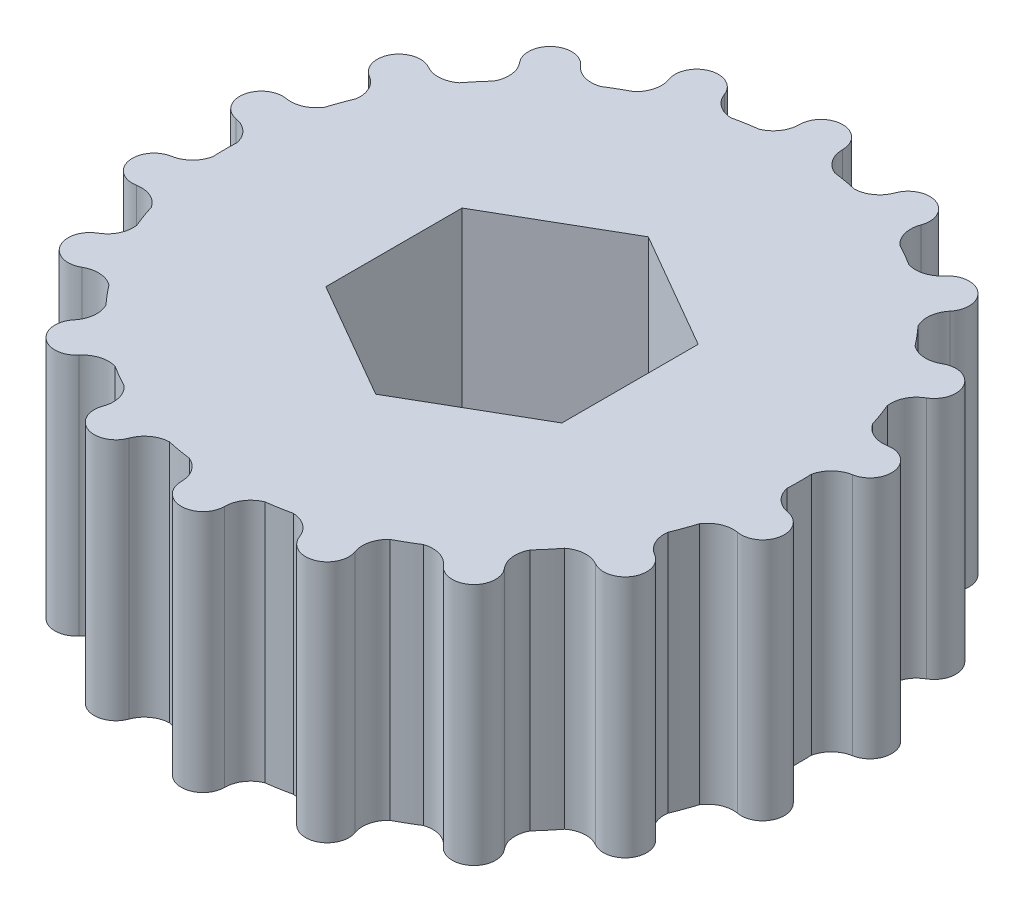
SolidWorks part; units mm, degrees
ref_plane "Front Plane" through (0, 0, 0) normal (0, 0, 1) x (1, 0, 0)
ref_plane "Top Plane" through (0, 0, 0) normal (0, 1, 0) x (1, 0, 0)
ref_plane "Right Plane" through (0, 0, 0) normal (1, 0, 0) x (0, 0, -1)
sketch "Sketch1" plane through (0, 0, 0) normal (0, 1, 0) x (1, 0, 0)
  line L0 (0, 0) -> (0, 5.6003) construction
  line L1 (0, 5.6003) -> (-4.85, 2.8001)
  line L2 (-4.85, 2.8001) -> (-4.85, -2.8001)
  line L3 (-4.85, -2.8001) -> (0, -5.6003)
  line L4 (0, -5.6003) -> (4.85, -2.8001)
  line L5 (4.85, -2.8001) -> (4.85, 2.8001)
  line L6 (4.85, 2.8001) -> (0, 5.6003)
  circle A0 centre (0, 0) radius 11.811
  circle A1 centre (0, 0) radius 4.85 construction
  dimension "D1" = 23.622
  dimension "D2" = 9.7
extrude "Boss-Extrude1" add sketch "Sketch1" along normal blind 10
sketch "Sketch2" plane through (0, 10, 0) normal (0, 1, 0) x (1, 0, 0)
  line L0 (0, 0) -> (0, 11.811) construction
  line L1 (0, 11.811) -> (0, 12.7) construction
  line L2 (0, 12.7) -> (0, 13.589) construction
  line L3 (-0.889, 12.7) -> (0.889, 12.7) construction
  circle A0 centre (0, 0) radius 11.811 construction
  arc A1 (-0.889, 12.7) -> (0.889, 12.7) centre (0, 12.7) cw
  arc A4 (-2.051, 11.6316) -> (2.051, 11.6316) centre (0, 0) cw
  arc A5 (-0.889, 12.7) -> (-2.051, 11.6316) centre (-1.9612, 12.7) cw
  arc A6 (0.889, 12.7) -> (2.051, 11.6316) centre (1.9612, 12.7) ccw
  point P13 (-1.9388, 11.6502)
  point P15 (-0.889, 12.7)
  point P16 (-1.6438, 11.696)
  point P17 (-1.7696, 11.6777)
  circle M1 centre (0, 0) radius 11.811
  dimension "D1" = 1.778
  dimension "D2" = 1.778
  dimension "D3" = 20
extrude "Boss-Extrude2" add sketch "Sketch2" against normal up to surface (10 mm away) contours A6 A1 A5 M1 up to face at (0, 0, 11.811)
pattern_circular "CirPattern1" count 18 over 360 about axis through (0, 0, 0) along (0, 1, 0) of "Boss-Extrude2"
